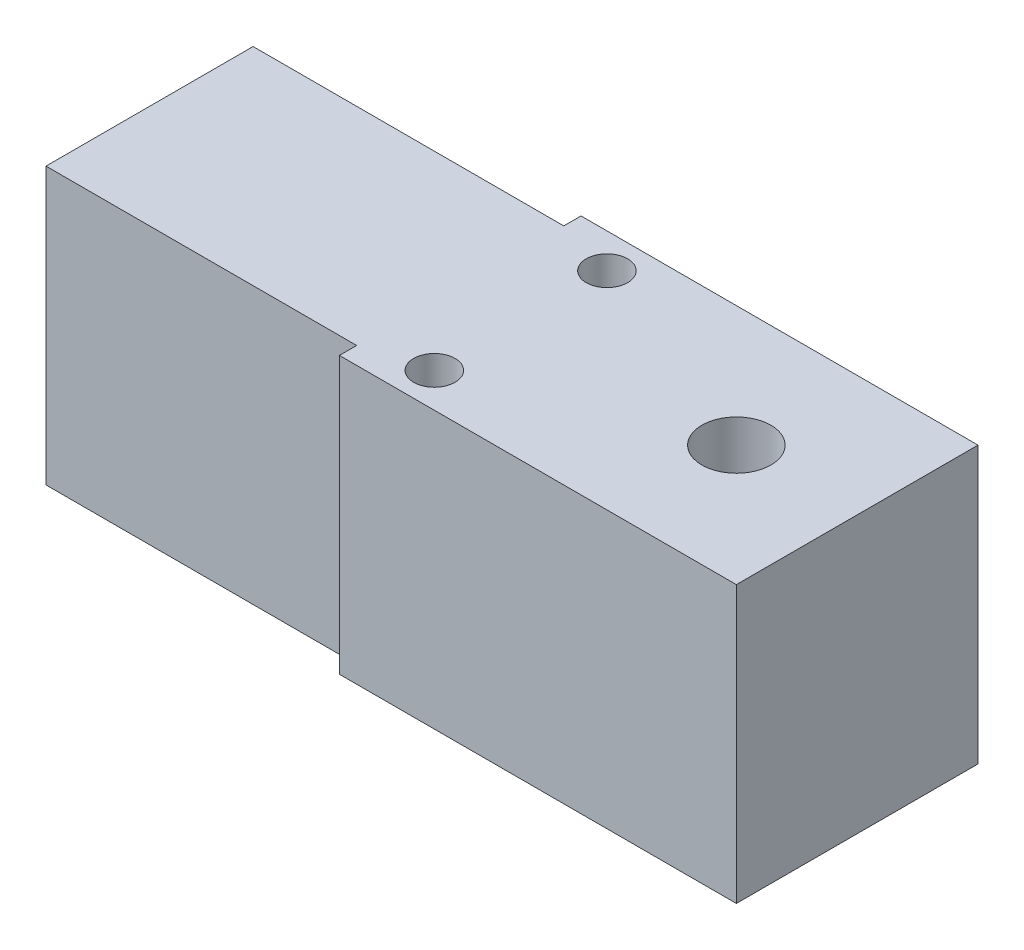
SolidWorks part; units mm, degrees
ref_plane "Front Plane" through (0, 0, 0) normal (0, 0, 1) x (1, 0, 0)
ref_plane "Top Plane" through (0, 0, 0) normal (0, 1, 0) x (1, 0, 0)
ref_plane "Right Plane" through (0, 0, 0) normal (1, 0, 0) x (0, 0, -1)
sketch "Sketch1" plane through (0, 0, 0) normal (0, 1, 0) x (1, 0, 0)
  line L0 (-28.575, 0) -> (36.5125, 0) construction
  line L1 (-28.575, -9.525) -> (0, -9.525)
  line L2 (-28.575, -9.525) -> (-28.575, 9.525)
  line L3 (-28.575, 9.525) -> (0, 9.525)
  line L4 (0, -9.525) -> (0, 9.525)
  line L5 (-28.575, -9.525) -> (0, 9.525) construction
  line L6 (-28.575, 9.525) -> (0, -9.525) construction
  line L7 (36.5125, -11.1125) -> (0, -11.1125)
  line L8 (36.5125, -11.1125) -> (36.5125, 11.1125)
  line L9 (36.5125, 11.1125) -> (0, 11.1125)
  line L10 (0, -11.1125) -> (0, 11.1125)
  line L11 (36.5125, -11.1125) -> (0, 11.1125) construction
  line L12 (36.5125, 11.1125) -> (0, -11.1125) construction
  point P0 (-14.2875, 0)
  point P5 (18.2563, 0)
  dimension "D1" = 28.575
  dimension "D2" = 36.5125
  dimension "D3" = 22.225
  dimension "D4" = 19.05
extrude "Boss-Extrude1" add sketch "Sketch1" along normal mid plane 25.4 contours L1 L4 L3 L2 | L10 L7 L8 L9 L4
sketch "Sketch2" plane through (0, 0, 0) normal (0, -1, 0) x (1, 0, 0)
  line L0 (36.5125, 11.1125) -> (36.5125, -11.1125) construction
  circle A0 centre (25.4, 0) radius 3.175
  point P5 (36.5125, 0)
  dimension "D1" = 6.35
  dimension "D2" = 11.1125
sketch "Sketch3" plane through (0, -12.7, 0) normal (0, -1, 0) x (1, 0, 0)
  line L0 (0, -9.525) -> (0, -11.1125) construction
  line L1 (5.5562, -7.9375) -> (5.5562, 7.9375) construction
  circle A0 centre (5.5562, 7.9375) radius 1.905
  circle A1 centre (5.5562, -7.9375) radius 1.905
  point P4 (0, 0)
  point P10 (5.5562, 0)
  dimension "D1" = 3.81
  dimension "D2" = 15.875
  dimension "D3" = 5.5562
extrude "Cut-Extrude1" cut sketch "Sketch3" against normal through all
extrude "Cut-Extrude4" cut sketch "Sketch2" against normal through all both and the other way through all
